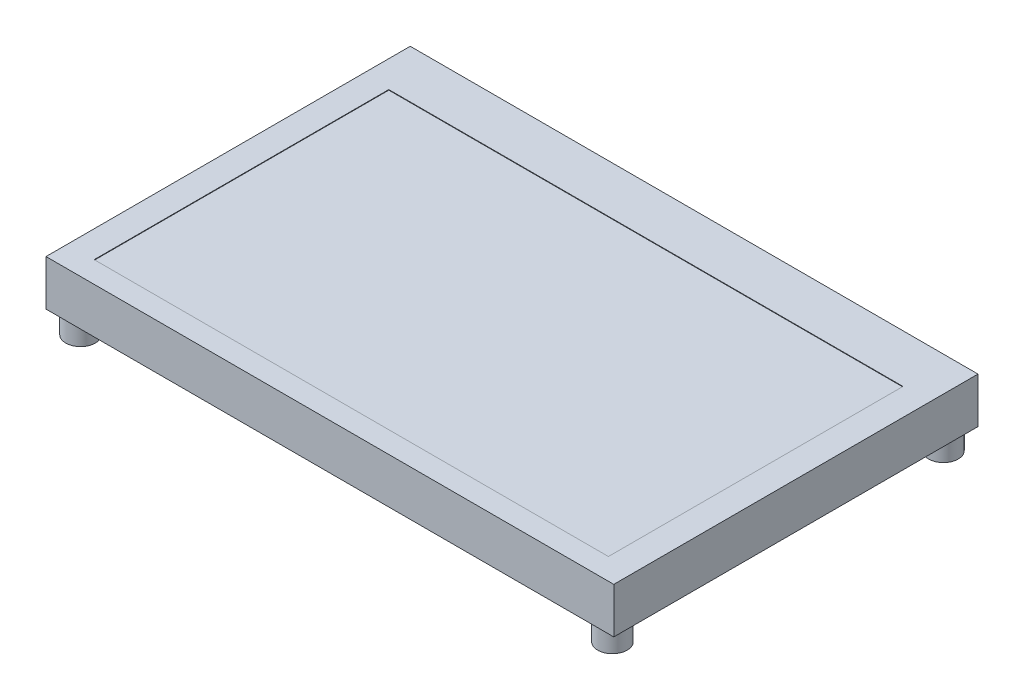
SolidWorks part; units mm, degrees
ref_plane "Front Plane" through (0, 0, 0) normal (0, 0, 1) x (1, 0, 0)
ref_plane "Top Plane" through (0, 0, 0) normal (0, 1, 0) x (1, 0, 0)
ref_plane "Right Plane" through (0, 0, 0) normal (1, 0, 0) x (0, 0, -1)
sketch "Sketch1" plane through (0, 0, 0) normal (0, 1, 0) x (1, 0, 0)
  line L1 (-53, -34) -> (53, -34)
  line L2 (-53, -34) -> (-53, 34)
  line L3 (-53, 34) -> (53, 34)
  line L4 (53, -34) -> (53, 34)
  line L5 (-53, -34) -> (53, 34) construction
  line L6 (-53, 34) -> (53, -34) construction
  point P0 (0, 0)
  dimension "D1" = 106
  dimension "D2" = 68
extrude "Boss-Extrude1" add sketch "Sketch1" along normal blind 8.5
sketch "Sketch2" plane through (0, 0, 0) normal (0, -1, 0) x (-1, 0, 0)
  line L1 (53, -34) -> (-53, -34) construction
  line L2 (53, 34) -> (53, -34) construction
  line L3 (-53, -34) -> (-53, 34) construction
  line L4 (-53, 34) -> (53, 34) construction
  circle A0 centre (49.65, -30.9) radius 2.75
  circle A1 centre (-49.65, -30.9) radius 2.75
  circle A2 centre (49.65, 30.9) radius 2.75
  circle A3 centre (-49.65, 30.9) radius 2.75
  circle A4 centre (27.38, -24.5) radius 2.75
  circle A5 centre (-30.62, -24.5) radius 2.75
  circle A6 centre (27.38, 24.54) radius 2.75
  circle A7 centre (-30.62, 24.54) radius 2.75
  dimension "D1" = 3.1
  dimension "D3" = 3.35
  dimension "D5" = 3.1
  dimension "D7" = 25.62
  dimension "D9" = 9.5
  dimension "D11" = 25.62
  dimension "D2" = 3.35
  dimension "D4" = 3.1
  dimension "D6" = 3.35
  dimension "D8" = 9.5
  dimension "D10" = 22.38
  dimension "D12" = 9.46
extrude "Boss-Extrude2" add sketch "Sketch2" along normal blind 4
sketch "Sketch3" plane through (0, -4, 0) normal (0, -1, 0) x (-1, 0, 0)
  point P0 (49.65, -30.9)
  point P1 (27.38, -24.5)
  point P3 (-30.62, -24.5)
  point P5 (-49.65, -30.9)
  point P7 (-49.65, 30.9)
  point P9 (-30.62, 24.54)
  point P11 (27.38, 24.54)
  point P13 (49.65, 30.9)
sketch "Sketch4" plane through (0, 8.5, 0) normal (0, 1, 0) x (1, 0, 0)
  line L0 (53, -34) -> (53, 34) construction
  line L1 (48, -30) -> (-48, -30)
  line L2 (48, -30) -> (48, 25)
  line L3 (48, 25) -> (-48, 25)
  line L4 (-48, -30) -> (-48, 25)
  line L5 (48, -30) -> (-48, 25) construction
  line L6 (48, 25) -> (-48, -30) construction
  line L7 (-53, 34) -> (-53, -34) construction
  line L8 (-53, -34) -> (53, -34) construction
  line L9 (53, 34) -> (-53, 34) construction
  point P4 (0, -2.5)
  dimension "D1" = 5
  dimension "D2" = 5
  dimension "D3" = 4
  dimension "D4" = 9
extrude "Cut-Extrude1" cut sketch "Sketch4" against normal blind 0.1
